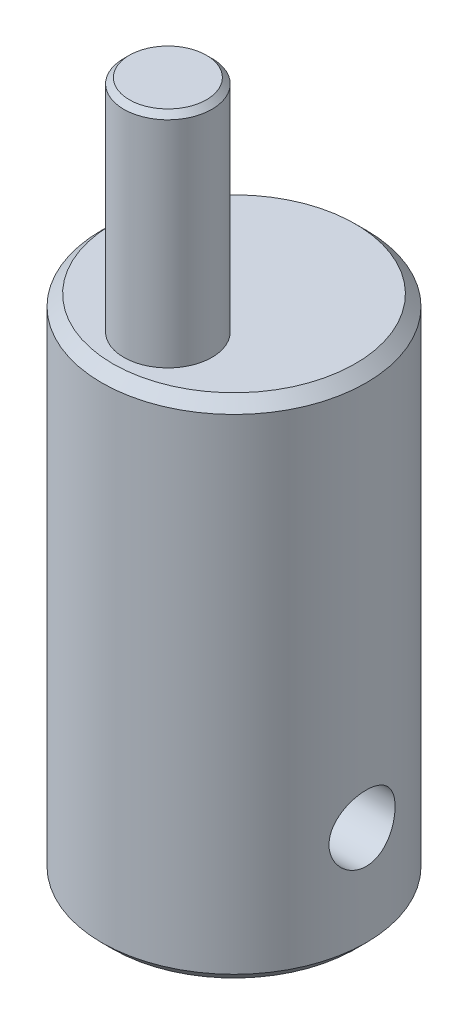
SolidWorks part; units mm, degrees
ref_plane "Front Plane" through (0, 0, 0) normal (0, 0, 1) x (1, 0, 0)
ref_plane "Top Plane" through (0, 0, 0) normal (0, 1, 0) x (1, 0, 0)
ref_plane "Right Plane" through (0, 0, 0) normal (1, 0, 0) x (0, 0, -1)
sketch "Sketch1" plane through (0, 0, 0) normal (0, 1, 0) x (1, 0, 0)
  circle A0 centre (0, 0) radius 6
  dimension "D1" = 12
extrude "Boss-Extrude1" add sketch "Sketch1" along normal blind 23
sketch "Sketch2" plane through (0, 23, 0) normal (0, 1, 0) x (1, 0, 0)
  circle A0 centre (0, -3) radius 2
  dimension "D1" = 4
  dimension "D2" = 3
extrude "Boss-Extrude2" add sketch "Sketch2" along normal blind 10
sketch "Sketch3" plane through (0, 0, 0) normal (1, 0, 0) x (0, 0, -1)
  circle A0 centre (0, 5) radius 1.5
  dimension "D1" = 5
  dimension "D2" = 3
extrude "Cut-Extrude1" cut sketch "Sketch3" against normal through all both and the other way through all
chamfer "Chamfer1" distance 0.25 angle 45 1 edges at (0, 33, 5)
chamfer "Chamfer2" distance 0.5 angle 45 2 edges at (0, 0, 6) (0, 23, 6)
